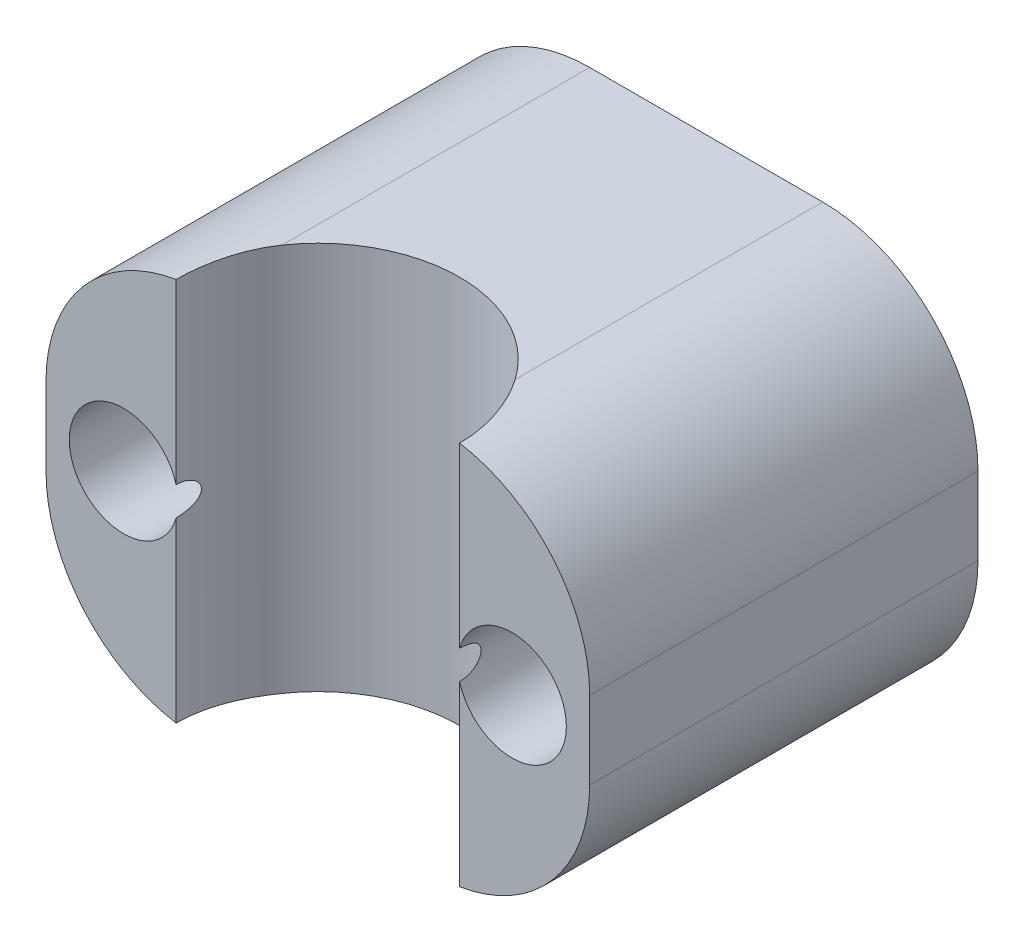
SolidWorks part; units mm, degrees
ref_plane "Front" through (0, 0, 0) normal (0, 0, 1) x (1, 0, 0)
ref_plane "Top" through (0, 0, 0) normal (0, 1, 0) x (1, 0, 0)
ref_plane "Right" through (0, 0, 0) normal (1, 0, 0) x (0, 0, -1)
sketch "Эскиз1" plane through (0, 0, 0) normal (0, 0, 1) x (1, 0, 0)
  line L1 (-3, 5) -> (3, 5)
  line L2 (-7, 1) -> (-7, -1)
  line L3 (-3, -5) -> (3, -5)
  line L4 (7, 1) -> (7, -1)
  line L5 (-7, 5) -> (7, -5) construction
  line L6 (-7, -5) -> (7, 5) construction
  arc A0 (3, -5) -> (7, -1) centre (3, -1) ccw
  arc A1 (3, 5) -> (7, 1) centre (3, 1) cw
  arc A2 (-7, -1) -> (-3, -5) centre (-3, -1) ccw
  arc A3 (-3, 5) -> (-7, 1) centre (-3, 1) ccw
  point P0 (0, 0)
  dimension "D3" = 4
  dimension "D1" = 14
  dimension "D2" = 10
extrude "Бобышка-Вытянуть1" add sketch "Эскиз1" along normal blind 10
sketch "Эскиз2" plane through (0, 5, 0) normal (0, 1, 0) x (1, 0, 0)
  line L0 (3, -10) -> (-3, -10) construction
  circle A0 centre (0, -10) radius 3.65
  dimension "D1" = 7.3
extrude "Вырез-Вытянуть1" cut sketch "Эскиз2" against normal up to next
sketch "Эскиз3" plane through (0, 0, 10) normal (0, 0, 1) x (1, 0, 0)
  line L0 (0, 5) -> (0, -5) construction
  line L1 (3, 5) -> (-3, 5) construction
  line L2 (-3, -5) -> (3, -5) construction
  line L3 (-5, 0) -> (5, 0) construction
  circle A0 centre (-5, 0) radius 1.4
  circle A1 centre (5, 0) radius 1.4
  point P10 (0, 0)
  dimension "D1" = 10
extrude "Вырез-Вытянуть2" cut sketch "Эскиз3" against normal up to next
